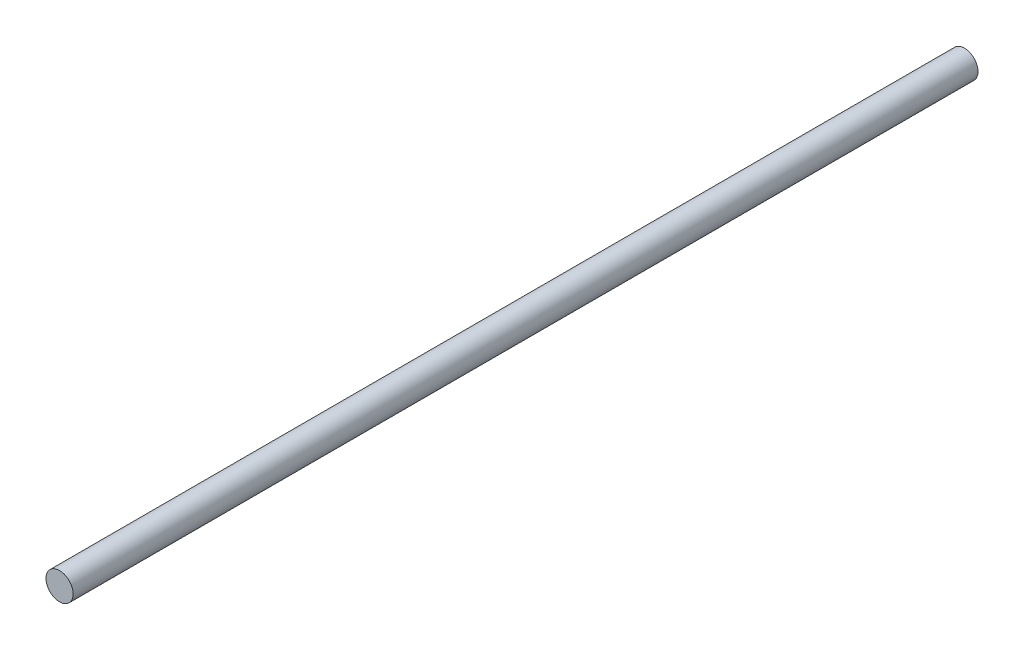
SolidWorks part; units mm, degrees
ref_plane "Plan de face" through (0, 0, 0) normal (0, 0, 1) x (1, 0, 0)
ref_plane "Plan de dessus" through (0, 0, 0) normal (0, 1, 0) x (1, 0, 0)
ref_plane "Plan de droite" through (0, 0, 0) normal (1, 0, 0) x (0, 0, -1)
sketch "Esquisse1" plane through (0, 0, 0) normal (0, 0, 1) x (1, 0, 0)
  circle A0 centre (0, 0) radius 1.5
  dimension "D1" = 3
extrude "Boss.-Extru.1" add sketch "Esquisse1" along normal blind 100
